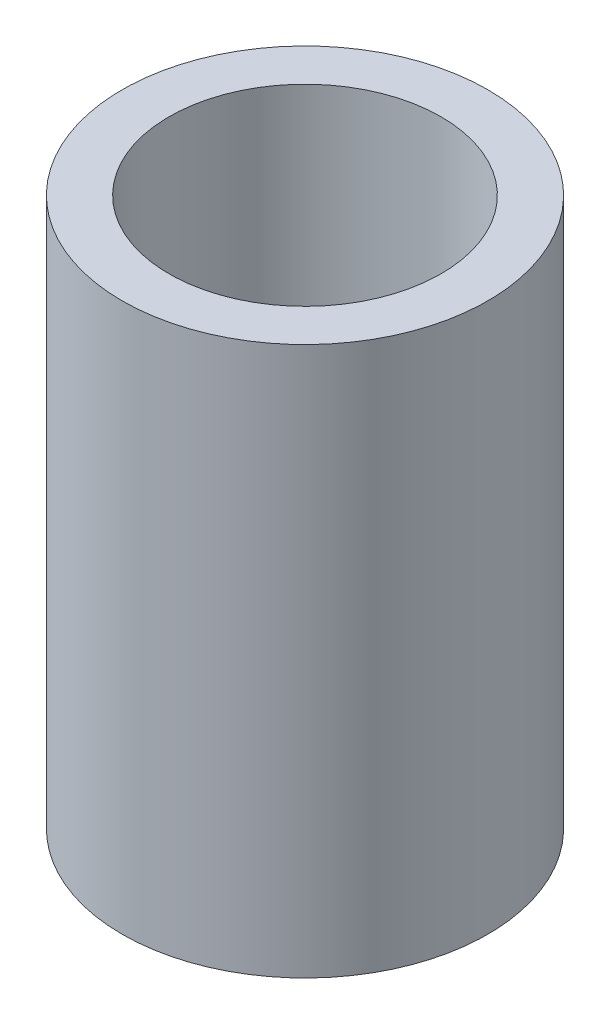
SolidWorks part; units mm, degrees
ref_plane "Front Plane" through (0, 0, 0) normal (0, 0, 1) x (1, 0, 0)
ref_plane "Top Plane" through (0, 0, 0) normal (0, 1, 0) x (1, 0, 0)
ref_plane "Right Plane" through (0, 0, 0) normal (1, 0, 0) x (0, 0, -1)
sketch "Sketch1" plane through (0, 0, 0) normal (0, 1, 0) x (1, 0, 0)
  circle A0 centre (0, 0) radius 3.175
  circle A1 centre (0, 0) radius 2.3622
  dimension "D1" = 6.35
  dimension "D2" = 4.7244
extrude "Boss-Extrude1" add sketch "Sketch1" along normal blind 9.525
